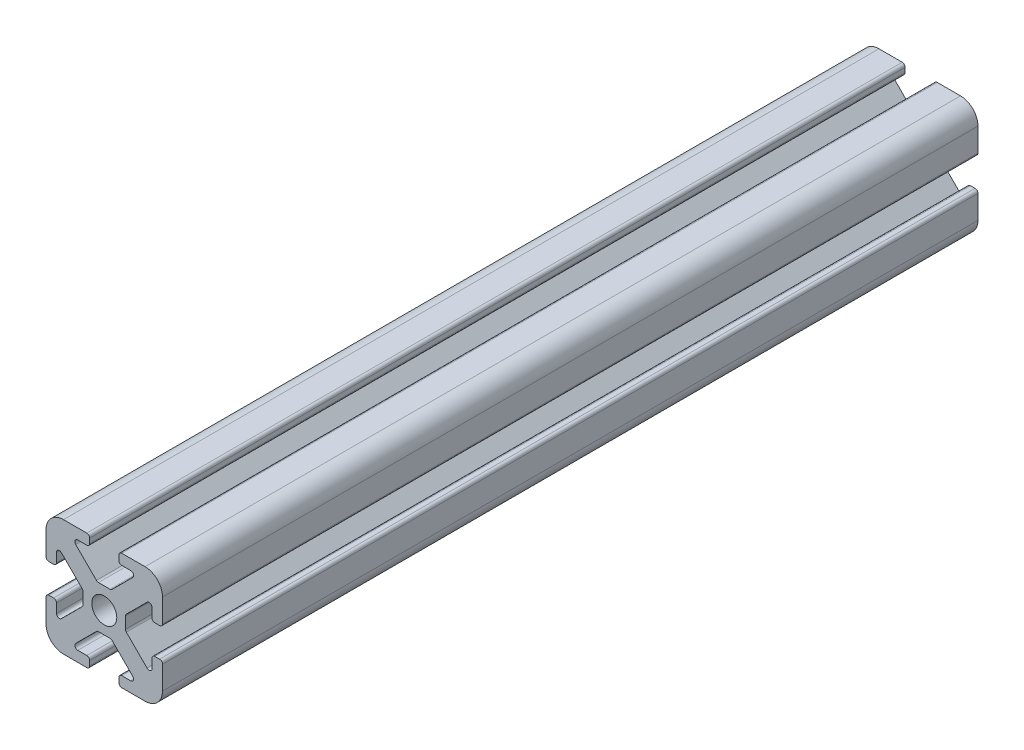
SolidWorks part; units mm, degrees
ref_plane "前视基准面" through (0, 0, 0) normal (0, 0, 1) x (1, 0, 0)
ref_plane "上视基准面" through (0, 0, 0) normal (0, 1, 0) x (1, 0, 0)
ref_plane "右视基准面" through (0, 0, 0) normal (1, 0, 0) x (0, 0, -1)
sketch "草图1" plane through (0, 0, 0) normal (0, 0, 1) x (1, 0, 0)
  line L1 (-3.65, 3.65) -> (3.65, 3.65)
  line L2 (-3.65, 3.65) -> (-3.65, -3.65)
  line L3 (-3.65, -3.65) -> (3.65, -3.65)
  line L4 (3.65, 3.65) -> (3.65, -3.65)
  circle A0 centre (0, 0) radius 2.15
  dimension "D5" = 4.3
  dimension "D1" = 7.3
  dimension "D2" = 3.65
  dimension "D3" = 3.65
  dimension "D4" = 7.3
extrude "凸台-拉伸1" add sketch "草图1" along normal blind 140
sketch "草图2" plane through (0, 0, 0) normal (0, 0, 1) x (1, 0, 0)
  line L0 (2.5, 10) -> (2.5, 8.2)
  line L1 (2.5, 8.2) -> (5.75, 8.2)
  line L2 (5.75, 8.2) -> (1.2, 3.65)
  line L3 (3.65, 3.65) -> (-3.65, 3.65) construction
  line L4 (1.2, 3.65) -> (3.65, 3.65)
  line L5 (3.65, 3.65) -> (3.65, 1.2)
  line L6 (3.65, -3.65) -> (3.65, 3.65) construction
  line L7 (3.65, 1.2) -> (8.2, 5.75)
  line L8 (8.2, 5.75) -> (8.2, 2.5)
  line L9 (8.2, 2.5) -> (10, 2.5)
  line L10 (10, 2.5) -> (10, 10)
  line L11 (10, 10) -> (2.5, 10)
  dimension "D1" = 1.8
  dimension "D2" = 1.8
  dimension "D3" = 6.35
  dimension "D4" = 6.35
  dimension "D5" = 2.5
  dimension "D6" = 5.75
  dimension "D7" = 5.75
  dimension "D8" = 2.5
extrude "凸台-拉伸2" add sketch "草图2" along normal blind 140
fillet "圆角1" radius 3 1 edges at (10, 10, 70)
fillet "圆角2" radius 0.5 6 edges at (8.2, 5.75, 70) (5.75, 8.2, 70) (8.2, 2.5, 70) (10, 2.5, 70) (2.5, 8.2, 70) (2.5, 10, 70)
pattern_circular "阵列(圆周)3" count 4 over 360 about axis through (0, 0, 0) along (0, 0, 1) of "圆角2", "圆角1", "凸台-拉伸2"
fillet "圆角3" radius 0.5 8 edges at (-3.65, -1.2, 70) (-3.65, 1.2, 70) (-1.2, -3.65, 70) (1.2, -3.65, 70) (-1.2, 3.65, 70) (1.2, 3.65, 70) (3.65, 1.2, 70) (3.65, -1.2, 70)
